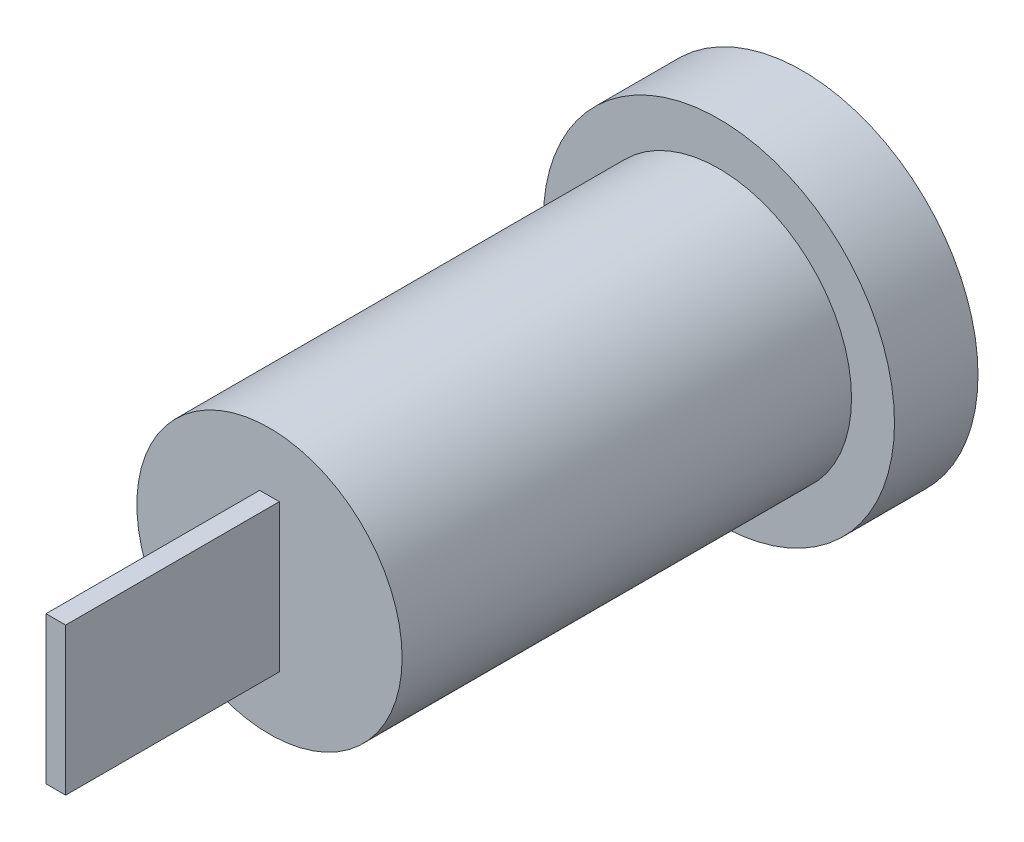
SolidWorks part; units mm, degrees
ref_plane "Plan de face" through (0, 0, 0) normal (0, 0, 1) x (1, 0, 0)
ref_plane "Plan de dessus" through (0, 0, 0) normal (0, 1, 0) x (1, 0, 0)
ref_plane "Plan de droite" through (0, 0, 0) normal (1, 0, 0) x (0, 0, -1)
sketch "Esquisse1" plane through (0, 0, 0) normal (0, 0, 1) x (1, 0, 0)
  circle A0 centre (0, 0) radius 5.4
  dimension "D1" = 10.8
extrude "Boss.-Extru.1" add sketch "Esquisse1" along normal blind 18.3
sketch "Esquisse2" plane through (0, 0, 0) normal (0, 0, -1) x (-1, 0, 0)
  circle A0 centre (0, 0) radius 7.15
  dimension "D1" = 14.3
extrude "Boss.-Extru.3" add sketch "Esquisse2" along normal blind 3.4
sketch "Esquisse3" plane through (0, 0, -3.4) normal (0, 0, -1) x (-1, 0, 0)
  circle A0 centre (0, 0) radius 3
  circle A1 centre (0, 0) radius 4.15
  circle A2 centre (0, 0) radius 7.15 construction
  dimension "D1" = 6
  dimension "D2" = 3
extrude "Enlèv. mat.-Extru.1" cut sketch "Esquisse3" against normal blind 3.4 contours A1 | A0
sketch "Esquisse5" plane through (0, 0, -3.4) normal (0, 0, -1) x (-1, 0, 0)
  circle A0 centre (0, 0) radius 2
  dimension "D1" = 4
extrude "Enlèv. mat.-Extru.2" cut sketch "Esquisse5" against normal blind 3.4
sketch "Esquisse6" plane through (0, 0, 18.3) normal (0, 0, 1) x (1, 0, 0)
  line L0 (0, 3) -> (0, -3) construction
  line L1 (0.4, 3) -> (-0.4, 3)
  line L2 (0.4, 3) -> (0.4, -3)
  line L3 (0.4, -3) -> (-0.4, -3)
  line L4 (-0.4, 3) -> (-0.4, -3)
  dimension "D1" = 6
  dimension "D2" = 0.8
extrude "Boss.-Extru.4" add sketch "Esquisse6" along normal blind 8.7
